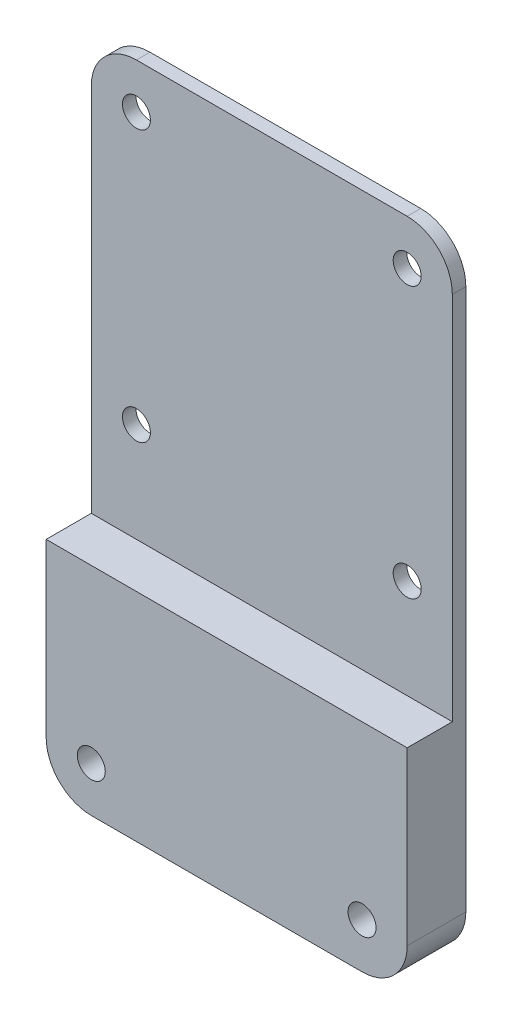
SolidWorks part; units mm, degrees
ref_plane "前视基准面" through (0, 0, 0) normal (0, 0, 1) x (1, 0, 0)
ref_plane "上视基准面" through (0, 0, 0) normal (0, 1, 0) x (1, 0, 0)
ref_plane "右视基准面" through (0, 0, 0) normal (1, 0, 0) x (0, 0, -1)
sketch "草图1" plane through (0, 0, 0) normal (0, 0, 1) x (1, 0, 0)
  line L1 (0, 0) -> (40, 0)
  line L2 (0, 0) -> (0, -70)
  line L3 (0, -70) -> (40, -70)
  line L4 (40, 0) -> (40, -70)
  circle A0 centre (5, -5) radius 1.55
  circle A1 centre (35, -5) radius 1.55
  circle A2 centre (5, -35) radius 1.55
  circle A3 centre (35, -35) radius 1.55
  circle A4 centre (5, -65) radius 1.55
  circle A5 centre (35, -65) radius 1.55
  dimension "D3" = 5
  dimension "D4" = 5
  dimension "D1" = 40
  dimension "D2" = 70
  dimension "D5" = 2
  dimension "D6" = 3
extrude "凸台-拉伸1" add sketch "草图1" along normal blind 1.5
sketch "草图2" plane through (0, 0, 1.5) normal (0, 0, 1) x (1, 0, 0)
  line L5 (0, 0) -> (0, -70) construction
  line L6 (0, -46) -> (40, -46)
  line L7 (0, -46) -> (0, -70)
  line L8 (0, -70) -> (40, -70)
  line L9 (40, -46) -> (40, -70)
  circle A0 centre (5, -35) radius 1.55 construction
  dimension "D1" = 11
extrude "凸台-拉伸2" add sketch "草图2" along normal blind 5
sketch "草图3" plane through (0, 0, 1.5) normal (0, 0, -1) x (-1, 0, 0)
  circle A0 centre (-35, -65) radius 1.55
  circle A1 centre (-5, -65) radius 1.55
extrude "切除-拉伸1" cut sketch "草图3" against normal blind 25
fillet "圆角1" radius 5 4 edges at (40, 0, 0.75) (0, 0, 0.75) (0, -70, 3.25) (40, -70, 3.25)
